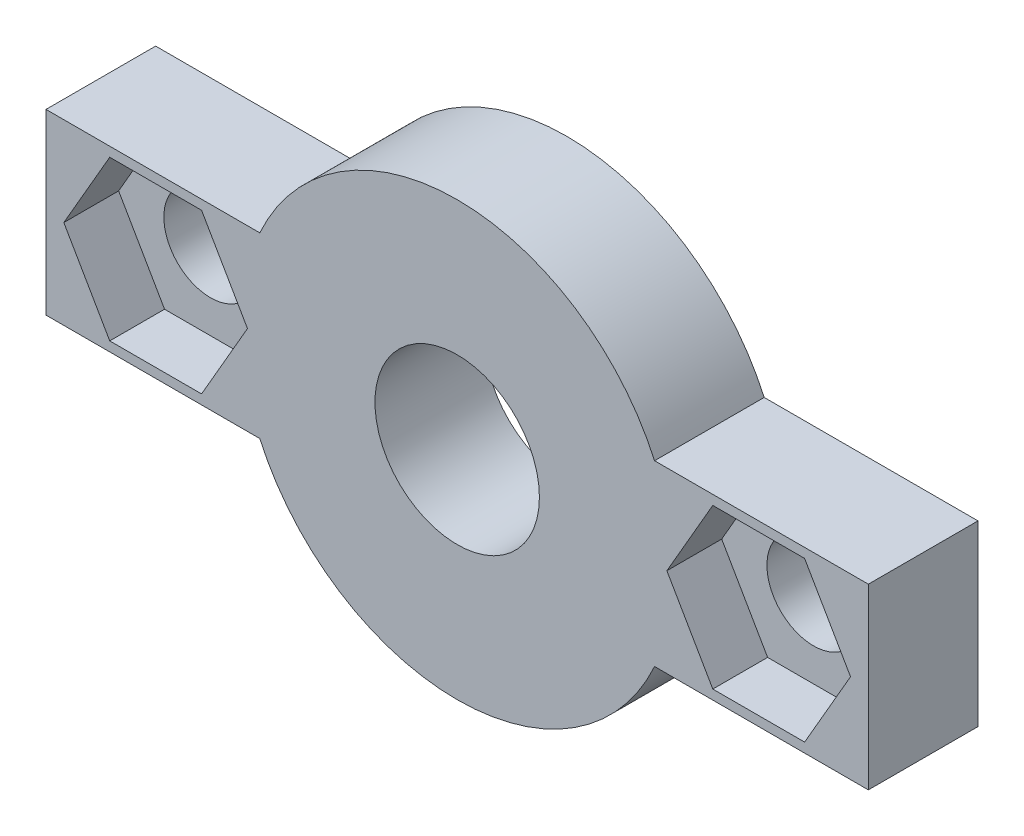
SolidWorks part; units mm, degrees
ref_plane "Alzado" through (0, 0, 0) normal (0, 0, 1) x (1, 0, 0)
ref_plane "Planta" through (0, 0, 0) normal (0, 1, 0) x (1, 0, 0)
ref_plane "Vista lateral" through (0, 0, 0) normal (1, 0, 0) x (0, 0, -1)
sketch "Croquis1" plane through (0, 0, 0) normal (0, 0, 1) x (1, 0, 0)
  line L0 (-7.2005, 3.25) -> (-15, 3.25)
  line L1 (15, -3.25) -> (7.2005, -3.25)
  line L2 (15, -3.25) -> (15, 3.25)
  line L3 (15, 3.25) -> (7.2005, 3.25)
  line L4 (-15, -3.25) -> (-15, 3.25)
  line L5 (15, -3.25) -> (-15, 3.25) construction
  line L6 (15, 3.25) -> (-15, -3.25) construction
  line L9 (-7.2005, -3.25) -> (-15, -3.25)
  arc A0 (-7.2005, -3.25) -> (7.2005, -3.25) centre (0, 0) ccw
  circle A1 centre (0, 0) radius 3
  arc A2 (7.2005, 3.25) -> (-7.2005, 3.25) centre (0, 0) ccw
  dimension "D3" = 6
  dimension "D4" = 7.9
  dimension "D1" = 30
  dimension "D2" = 6.5
extrude "Saliente-Extruir1" add sketch "Croquis1" along normal blind 4
sketch "Croquis2" plane through (0, 0, 4) normal (0, 0, 1) x (1, 0, 0)
  line L0 (-11, 0) -> (11, 0) construction
  line L1 (-15, -3.25) -> (-7.2005, -3.25) construction
  line L2 (-14.35, 0) -> (-12.675, -2.9012)
  line L3 (-12.675, -2.9012) -> (-9.325, -2.9012)
  line L4 (-9.325, -2.9012) -> (-7.65, 0)
  line L5 (-7.65, 0) -> (-9.325, 2.9012)
  line L6 (-9.325, 2.9012) -> (-12.675, 2.9012)
  line L7 (-12.675, 2.9012) -> (-14.35, 0)
  line L8 (14.35, 0) -> (12.675, 2.9012)
  line L9 (12.675, 2.9012) -> (9.325, 2.9012)
  line L10 (9.325, 2.9012) -> (7.65, 0)
  line L11 (7.65, 0) -> (9.325, -2.9012)
  line L12 (9.325, -2.9012) -> (12.675, -2.9012)
  line L13 (12.675, -2.9012) -> (14.35, 0)
  circle A2 centre (-11, 0) radius 3.35 construction
  circle A3 centre (11, 0) radius 3.35 construction
  point P2 (0, 0)
  dimension "D1" = 6.7
  dimension "D2" = 22
extrude "Cortar-Extruir1" cut sketch "Croquis2" against normal blind 2
sketch "Croquis3" plane through (0, 0, 4) normal (0, 0, 1) x (1, 0, 0)
  line L1 (-11, 0) -> (11, 0) construction
  circle A0 centre (-11, 0) radius 1.7
  circle A1 centre (11, 0) radius 1.7
  point P9 (0, 0)
  dimension "D1" = 3.4
  dimension "D2" = 22
extrude "Cortar-Extruir2" cut sketch "Croquis3" against normal blind 10
